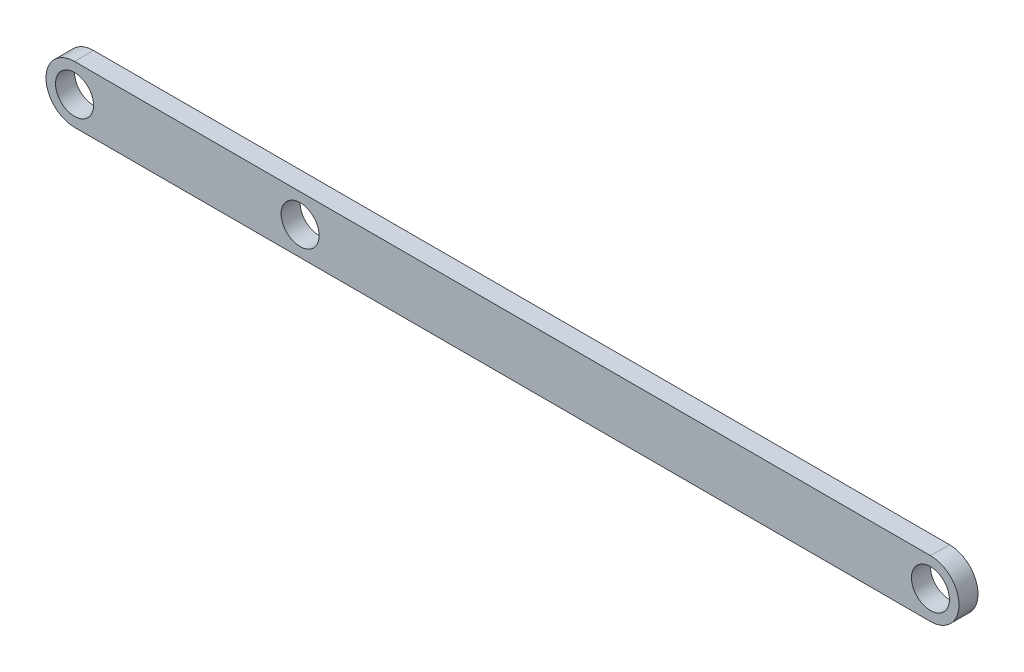
SolidWorks part; units mm, degrees
ref_plane "Спереди" through (0, 0, 0) normal (0, 0, 1) x (1, 0, 0)
ref_plane "Сверху" through (0, 0, 0) normal (0, 1, 0) x (1, 0, 0)
ref_plane "Справа" through (0, 0, 0) normal (1, 0, 0) x (0, 0, -1)
sketch "Эскиз1" plane through (0, 0, 0) normal (0, 0, 1) x (1, 0, 0)
  line L0 (0, 0) -> (-450, 0)
  line L1 (0, 30) -> (-450, 30)
  arc A0 (0, 0) -> (0, 30) centre (0, 15) ccw
  arc A1 (-450, 30) -> (-450, 0) centre (-450, 15) ccw
  point P5 (0, 0)
  dimension "D1" = 450
  dimension "D2" = 30
extrude "Бобышка-Вытянуть2" add sketch "Эскиз1" along normal blind 10 contours A1 L0 A0 L1
sketch "Эскиз2" plane through (0, 0, 0) normal (0, 0, -1) x (-1, 0, 0)
  circle A0 centre (0, 15) radius 10
  circle A1 centre (450, 15) radius 10
  dimension "D1" = 20
  dimension "D2" = 20
extrude "Вырез-Вытянуть1" cut sketch "Эскиз2" against normal blind 10
sketch "Эскиз4" plane through (0, 0, 10) normal (0, 0, 1) x (1, 0, 0)
  circle A0 centre (-331.4084, 15) radius 10
  circle A1 centre (-450, 15) radius 10 construction
  circle A2 centre (-450, 15) radius 10 construction
  point P2 (0, 0)
  dimension "D1" = 118.5916
extrude "Вырез-Вытянуть3" cut sketch "Эскиз4" against normal blind 10 contours A0
